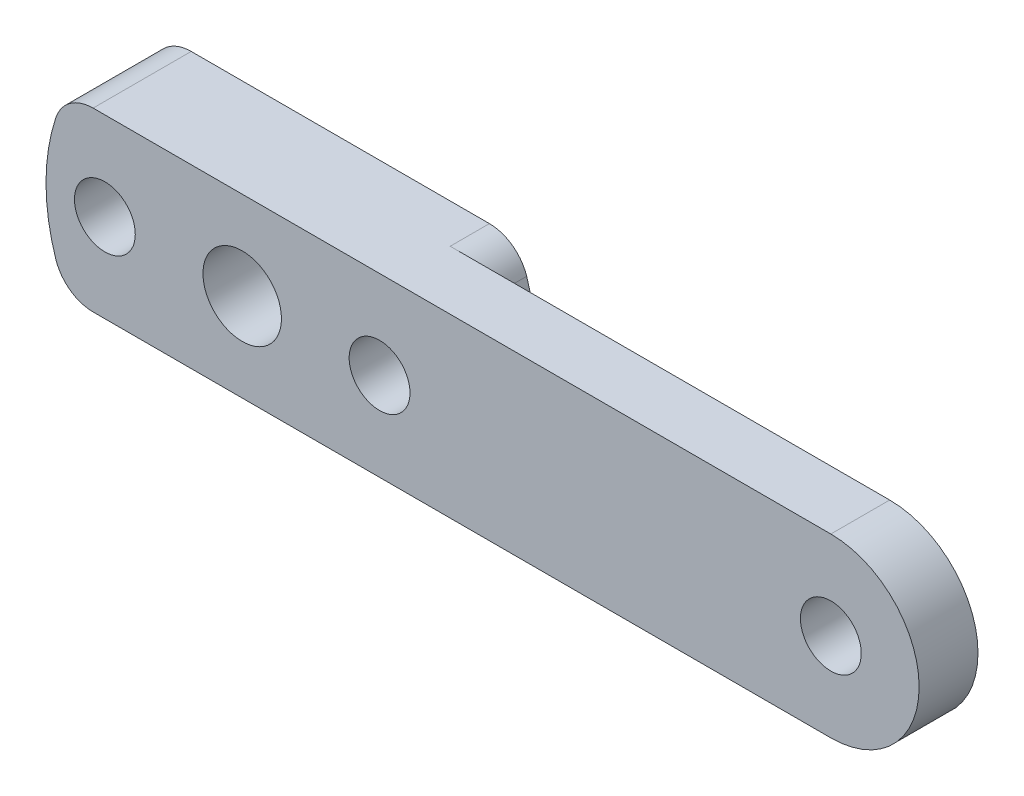
SolidWorks part; units mm, degrees
ref_plane "Front Plane" through (0, 0, 0) normal (0, 0, 1) x (1, 0, 0)
ref_plane "Top Plane" through (0, 0, 0) normal (0, 1, 0) x (1, 0, 0)
ref_plane "Right Plane" through (0, 0, 0) normal (1, 0, 0) x (0, 0, -1)
sketch "Sketch1" plane through (0, 0, 0) normal (0, 0, 1) x (1, 0, 0)
  line L0 (-8.9303, 4.5) -> (30, 4.5)
  line L1 (30, -4.5) -> (-8.9303, -4.5)
  line L2 (-7, 0) -> (7, 0) construction
  arc A0 (-8.9303, -4.5) -> (-8.9303, 4.5) centre (0, 0) cw
  arc A1 (30, 4.5) -> (30, -4.5) centre (30, 0) cw
  circle A2 centre (-7, 0) radius 1.55
  circle A3 centre (7, 0) radius 1.55
  circle A4 centre (30, 0) radius 1.55
  circle A5 centre (0, 0) radius 2
  point P6 (-10, 0)
  point P12 (0, 0)
  dimension "D1" = 10
  dimension "D2" = 9
  dimension "D4" = 3.1
  dimension "D6" = 4
  dimension "D3" = 30
  dimension "D5" = 14
extrude "Boss-Extrude1" add sketch "Sketch1" along normal mid plane 5
sketch "Sketch2" plane through (0, 0, -2.5) normal (0, 0, -1) x (-1, 0, 0)
  line L0 (8.9303, -4.5) -> (-30, -4.5) construction
  line L1 (-30, 4.5) -> (8.9303, 4.5) construction
  line L2 (-30, 4.5) -> (-8.9303, 4.5)
  line L3 (-8.9303, -4.5) -> (-30, -4.5)
  arc A0 (-30, 4.5) -> (-30, -4.5) centre (-30, 0) ccw construction
  arc A1 (-30, 4.5) -> (-30, -4.5) centre (-30, 0) ccw
  arc A2 (-8.9303, -4.5) -> (-8.9303, 4.5) centre (0, 0) cw
  dimension "D1" = 10
extrude "Cut-Extrude1" cut sketch "Sketch2" against normal offset from surface (2 mm away) 3 up to face at (11.3924, 0, 2.5)
fillet "Fillet1" radius 2 4 edges at (-8.9303, -4.5, 0) (-8.9303, 4.5, 0) (8.9303, -4.5, -1.5) (8.9303, 4.5, -1.5)
sketch "Sketch3" plane through (0, 0, -2.5) normal (0, 0, -1) x (-1, 0, 0)
  point P0 (0, 0)
sketch "Sketch4" plane through (0, 0, 2.5) normal (0, 0, 1) x (1, 0, 0)
  circle A0 centre (30, 0) radius 1.55 construction
  circle A1 centre (30, 0) radius 1.55
  point P4 (30, 0)
